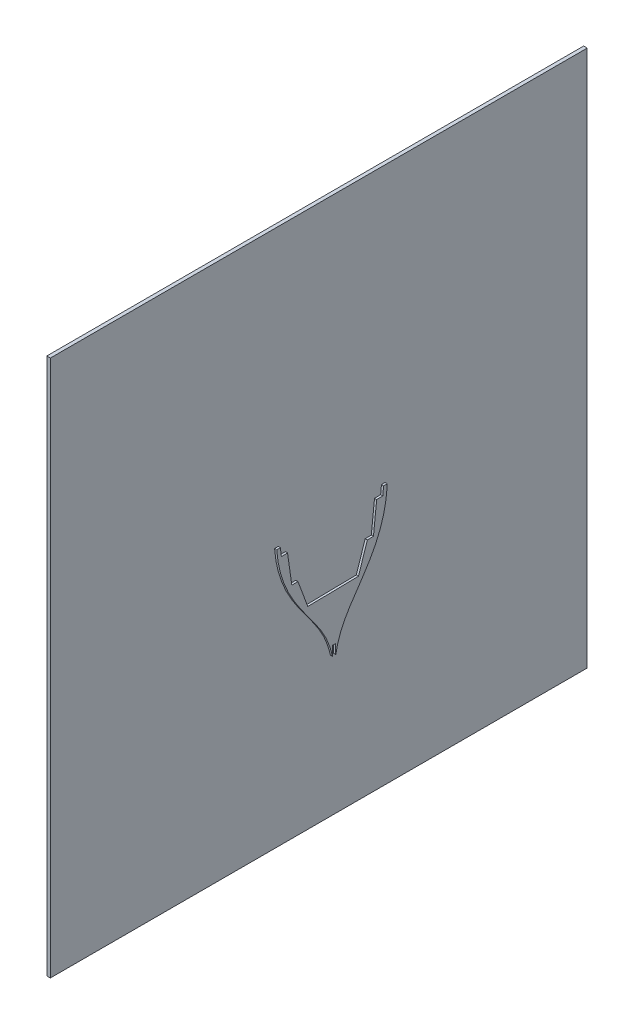
SolidWorks part; units mm, degrees
ref_plane "Plan de face" through (0, 0, 0) normal (0, 0, 1) x (1, 0, 0)
ref_plane "Plan de dessus" through (0, 0, 0) normal (0, 1, 0) x (1, 0, 0)
ref_plane "Plan de droite" through (0, 0, 0) normal (1, 0, 0) x (0, 0, -1)
sketch "Esquisse1" plane through (0, 0, 0) normal (0, 0, 1) x (1, 0, 0)
  point P0 (-20, 0)
  dimension "D1" = 20
sketch3d "Esquisse3D1"
  line L1 (-20, 1121.2893, 777.275) -> (-20, 1121.2893, -722.725)
  line L2 (-20, 1121.2893, 777.275) -> (-20, -378.7107, 777.275)
  line L3 (-20, -378.7107, 777.275) -> (-20, -378.7107, -722.725)
  line L4 (-20, 1121.2893, -722.725) -> (-20, -378.7107, -722.725)
  dimension "D1" = 1500
  dimension "D2" = 1500
extrude "Boss.-Extru.2" add sketch "Esquisse3D1" along direction (1, 0, 0) on the side of the normal blind 10 contours L2 L1 L4 L3
sketch "Esquisse4" plane through (-10, 0, 0) normal (1, 0, 0) x (0, 0, -1)
  line L0 (0, 0) -> (-7.701, 425.1082) construction
  line L1 (169.3944, 339.9131) -> (-188.5193, 333.4294) construction
  line L2 (-187.2006, 249.23) -> (169.0622, 255.6839) construction
  line L3 (-144.268, 175.2448) -> (126.4811, 180.1495) construction
sketch "Esquisse5" plane through (0, 0, 0) normal (1, 0, 0) x (0, 0, -1)
  line L0 (-7.701, 425.1082) -> (0, 0) construction
  line L2 (0, 0) -> (12.3908, 60.8511) construction
  line L3 (12.3908, 60.8511) -> (14.8702, 131.7605) construction
  line L4 (14.8702, 131.7605) -> (141.2845, 182.2261) construction
  line L5 (141.2845, 182.2261) -> (147.6987, 362.6712) construction
  line L8 (147.6987, 362.6712) -> (137.6987, 362.4901)
  line L9 (137.6987, 362.4901) -> (135.5219, 339.2995)
  line L10 (169.3944, 339.9131) -> (-188.5193, 333.4294) construction
  line L11 (135.5219, 339.2995) -> (118.4113, 338.9895)
  line L12 (118.4113, 338.9895) -> (109.4452, 254.6039)
  line L13 (-187.2006, 249.23) -> (169.0622, 255.6839) construction
  line L14 (109.4452, 254.6039) -> (92.374, 254.2946)
  line L15 (92.374, 254.2946) -> (67.5627, 179.0822)
  line L16 (-144.268, 175.2448) -> (126.4811, 180.1495) construction
  line L17 (67.5627, 179.0822) -> (-74.0045, 176.5176)
  line L18 (0, 0) -> (-14.5867, 60.3624) construction
  line L19 (-14.5867, 60.3624) -> (-19.6327, 131.1354) construction
  line L20 (-19.6327, 131.1354) -> (-147.7918, 176.9893) construction
  line L21 (-147.7918, 176.9893) -> (-160.7373, 357.0838) construction
  line L22 (-101.5236, 250.7821) -> (-74.0045, 176.5176)
  line L23 (-118.5949, 250.4729) -> (-101.5236, 250.7821)
  line L24 (-130.6114, 334.4784) -> (-118.5949, 250.4729)
  line L25 (-147.722, 334.1684) -> (-130.6114, 334.4784)
  line L26 (-150.7373, 357.2649) -> (-147.722, 334.1684)
  line L27 (-160.7373, 357.0838) -> (-150.7373, 357.2649)
  spline S0 degree 4 poles (0, 0) (12.3908, 60.8511) (14.8702, 131.7605) (141.2845, 182.2261) (147.6987, 362.6712) knots 0 0 0 0 0 1 1 1 1 1
  spline S1 degree 4 poles (0, 0) (-14.5867, 60.3624) (-19.6327, 131.1354) (-147.7918, 176.9893) (-160.7373, 357.0838) knots 0 0 0 0 0 1 1 1 1 1
  point P30 (-3.2209, 177.7999)
  dimension "D1" = 10
extrude "Boss.-Extru.3" add sketch "Esquisse5" along normal blind 6 separate body
sketch "Esquisse6" plane through (6, 0, 0) normal (1, 0, 0) x (0, 0, -1)
  line L0 (-4.8823, 21.0241) -> (-5.3715, 48.0241)
  line L1 (-5.3715, 48.0241) -> (3.6285, 48.1871)
  line L2 (3.6285, 48.1871) -> (4.1177, 21.1871)
  line L3 (4.1177, 21.1871) -> (117.0633, -47.527)
  line L4 (117.0633, -47.527) -> (-85.2277, -65.22)
  line L5 (-85.2277, -65.22) -> (-4.8823, 21.0241)
  line L6 (-4.8823, 21.0241) -> (4.1177, 21.1871) construction
  line L7 (-144.268, 175.2448) -> (126.4811, 180.1495) construction
  spline S0 degree 4 poles (-160.7373, 357.0838) (-147.7918, 176.9893) (-19.6327, 131.1354) (-14.5867, 60.3624) (0, 0) knots 0 0 0 0 0 1 1 1 1 1 construction
  spline S1 degree 4 poles (0, 0) (12.3908, 60.8511) (14.8702, 131.7605) (141.2845, 182.2261) (147.6987, 362.6712) knots 0 0 0 0 0 1 1 1 1 1 construction
  dimension "D1" = 9
  dimension "D2" = 27
extrude "Enlèv. mat.-Extru.1" cut sketch "Esquisse6" against normal blind 6
